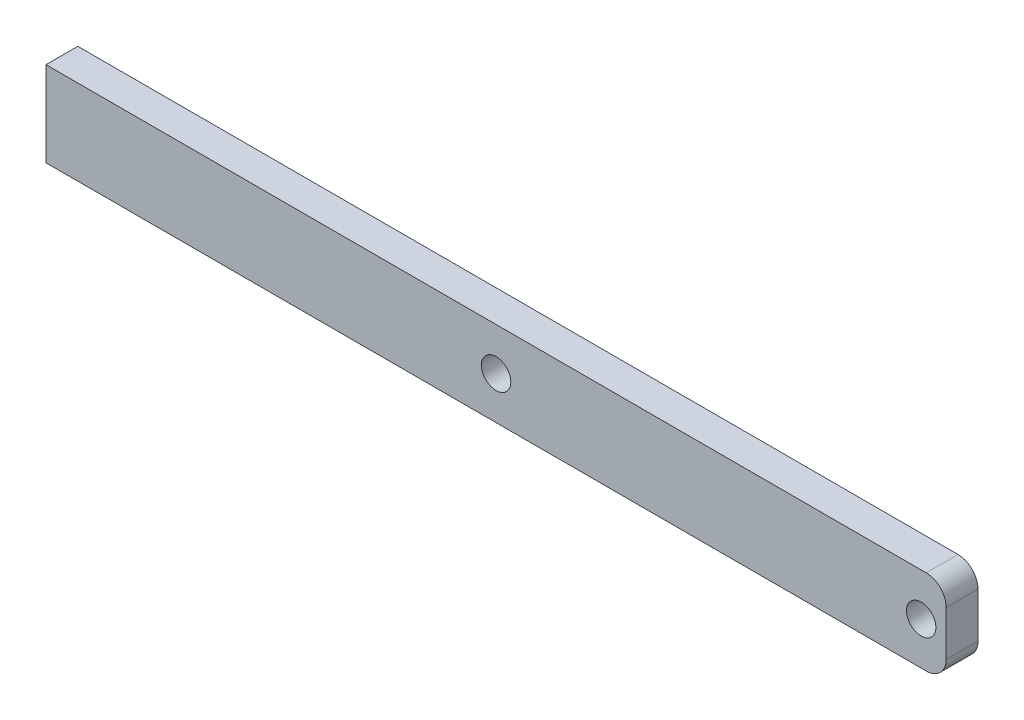
SolidWorks part; units mm, degrees
ref_plane "Front Plane" through (0, 0, 0) normal (0, 0, 1) x (1, 0, 0)
ref_plane "Top Plane" through (0, 0, 0) normal (0, 1, 0) x (1, 0, 0)
ref_plane "Right Plane" through (0, 0, 0) normal (1, 0, 0) x (0, 0, -1)
sketch "Sketch1" plane through (0, 0, 0) normal (0, 0, 1) x (1, 0, 0)
  line L0 (90, 4.25) -> (26.5061, 4.25) construction
  line L1 (0, 0) -> (90, 0)
  line L2 (0, 0) -> (0, 8.5)
  line L3 (0, 8.5) -> (90, 8.5)
  line L4 (90, 0) -> (90, 8.5)
  circle A0 centre (87.5, 4.25) radius 1.47
  dimension "D3" = 2.94
  dimension "D4" = 2.5
  dimension "D5" = 90
  dimension "D1" = 8.5
  dimension "D2" = 90
extrude "Boss-Extrude1" add sketch "Sketch1" along normal blind 3.18
sketch "Sketch2" plane through (0, 0, 3.18) normal (0, 0, 1) x (1, 0, 0)
  line L2 (90, 0) -> (90, 8.5) construction
  line L3 (43.53, 4.25) -> (90, 4.25) construction
  circle A1 centre (45, 4.25) radius 1.47
  dimension "D4" = 45
  dimension "D3" = 2.94
extrude "Cut-Extrude1" cut sketch "Sketch2" against normal through all
fillet "Fillet1" radius 2 2 edges at (90, 0, 1.59) (90, 8.5, 1.59)
